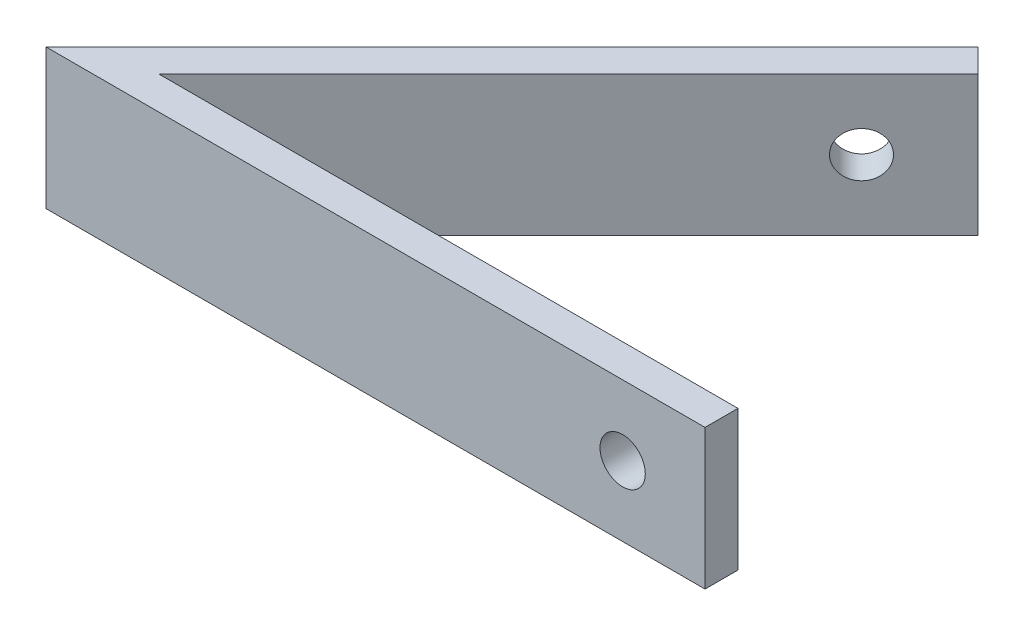
SolidWorks part; units mm, degrees
ref_plane "前视基准面" through (0, 0, 0) normal (0, 0, 1) x (1, 0, 0)
ref_plane "上视基准面" through (0, 0, 0) normal (0, 1, 0) x (1, 0, 0)
ref_plane "右视基准面" through (0, 0, 0) normal (1, 0, 0) x (0, 0, -1)
sketch "草图1" plane through (0, 0, 0) normal (0, 1, 0) x (1, 0, 0)
  line L0 (80, 0) -> (0, 0)
  line L1 (0, 0) -> (56.5685, 56.5685)
  line L2 (80, 4) -> (9.6569, 4)
  line L3 (9.6569, 4) -> (59.397, 53.7401)
  line L4 (80, 0) -> (80, 4)
  line L5 (56.5685, 56.5685) -> (59.397, 53.7401)
  dimension "D1" = 80
  dimension "D2" = 80
  dimension "D3" = 45
  dimension "D4" = 4
extrude "凸台-拉伸1" add sketch "草图1" along normal blind 17
sketch "草图2" plane through (2.8284, 0, 2.8284) normal (0.7071, 0, 0.7071) x (0.7071, 0, -0.7071)
  line L0 (9.6569, 17) -> (80, 17) construction
  line L1 (80, 17) -> (80, 0) construction
  circle A0 centre (70, 8.5) radius 2.75
  dimension "D1" = 8.5
  dimension "D2" = 10
  dimension "D3" = 5.5
extrude "切除-拉伸1" cut sketch "草图2" against normal blind 17
sketch "草图3" plane through (0, 0, 0) normal (0, 0, 1) x (1, 0, 0)
  line L0 (0, 0) -> (80, 0) construction
  line L1 (80, 17) -> (80, 0) construction
  circle A0 centre (70, 8.5) radius 2.75
  dimension "D1" = 8.5
  dimension "D2" = 10
  dimension "D3" = 5.5
extrude "切除-拉伸2" cut sketch "草图3" against normal blind 17
